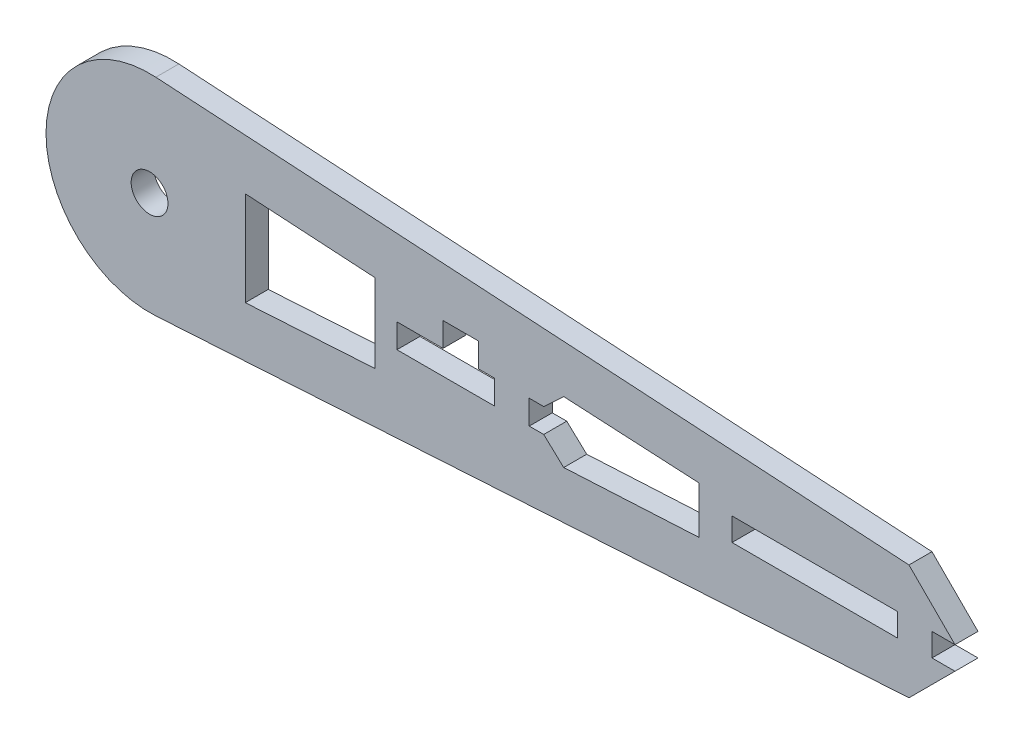
SolidWorks part; units mm, degrees
ref_plane "前视基准面" through (0, 0, 0) normal (0, 0, 1) x (1, 0, 0)
ref_plane "上视基准面" through (0, 0, 0) normal (0, 1, 0) x (1, 0, 0)
ref_plane "右视基准面" through (0, 0, 0) normal (1, 0, 0) x (0, 0, -1)
sketch "草图1" plane through (0, 0, 0) normal (0, 0, 1) x (1, 0, 0)
  line L0 (68, 1) -> (70, 1)
  line L1 (70, 1) -> (66, 5)
  line L2 (66, 5) -> (0.5467, 8.9834)
  line L3 (30, 1.05) -> (28.6, 1.05)
  line L4 (28.6, 1.05) -> (28.6, 3.15)
  line L5 (25.5, 1.05) -> (21.5, 1.05)
  line L6 (21.5, 1.05) -> (21.5, -1.05)
  line L7 (28.6, 3.15) -> (25.5, 3.15)
  line L8 (25.5, 3.15) -> (25.5, 1.05)
  line L9 (0.5467, -8.9834) -> (66, -5)
  line L10 (66, -5) -> (70, -1)
  line L11 (70, -1) -> (68, -1)
  line L12 (68, -1) -> (68, 1)
  line L13 (25, 0) -> (61.3378, 0) construction
  line L14 (21.5, -1.05) -> (30, -1.05)
  line L15 (8.3178, 4.1016) -> (19.5823, 3.4204)
  line L16 (30, 1.05) -> (30, -1.05)
  line L17 (19.5823, 3.4204) -> (19.5823, -3.4204)
  line L18 (19.5823, -3.4204) -> (8.3178, -4.1016)
  line L19 (8.3178, -4.1016) -> (8.3178, 4.1016)
  line L20 (65, 1) -> (65, -1)
  line L21 (65, -1) -> (50.622, -1)
  line L22 (50.622, 1) -> (65, 1)
  line L23 (50.622, -1) -> (50.622, 1)
  line L24 (47.7523, -2.05) -> (35.9939, -2.6692)
  line L25 (47.7523, 2.05) -> (47.7523, -2.05)
  line L26 (34.2566, -1.05) -> (32.9988, -1.05)
  line L27 (34.2566, -1.05) -> (35.9939, -2.6692)
  line L28 (35.9939, 2.6692) -> (34.2566, 1.05)
  line L29 (35.9939, 2.6692) -> (47.7523, 2.05)
  line L30 (32.9988, 1.05) -> (34.2566, 1.05)
  line L31 (32.9988, 1.05) -> (32.9988, -1.05)
  arc A1 (0.5467, 8.9834) -> (0.5467, -8.9834) centre (0, 0) ccw
  circle A3 centre (0, 0) radius 1.6
  dimension "D8" = 9
  dimension "D9" = 4
  dimension "D13" = 30
  dimension "D6" = 3.2
  dimension "D16" = 65
  dimension "D1" = 2.1
  dimension "D2" = 2
  dimension "D3" = 3
  dimension "D4" = 25
  dimension "D5" = 70
  dimension "D7" = 10
  dimension "D10" = 3.1
  dimension "D11" = 2.9988
  dimension "D12" = 2.1
  dimension "D14" = 8.5
  dimension "D15" = 4.5
extrude "凸台-拉伸1" add sketch "草图1" along normal blind 2
